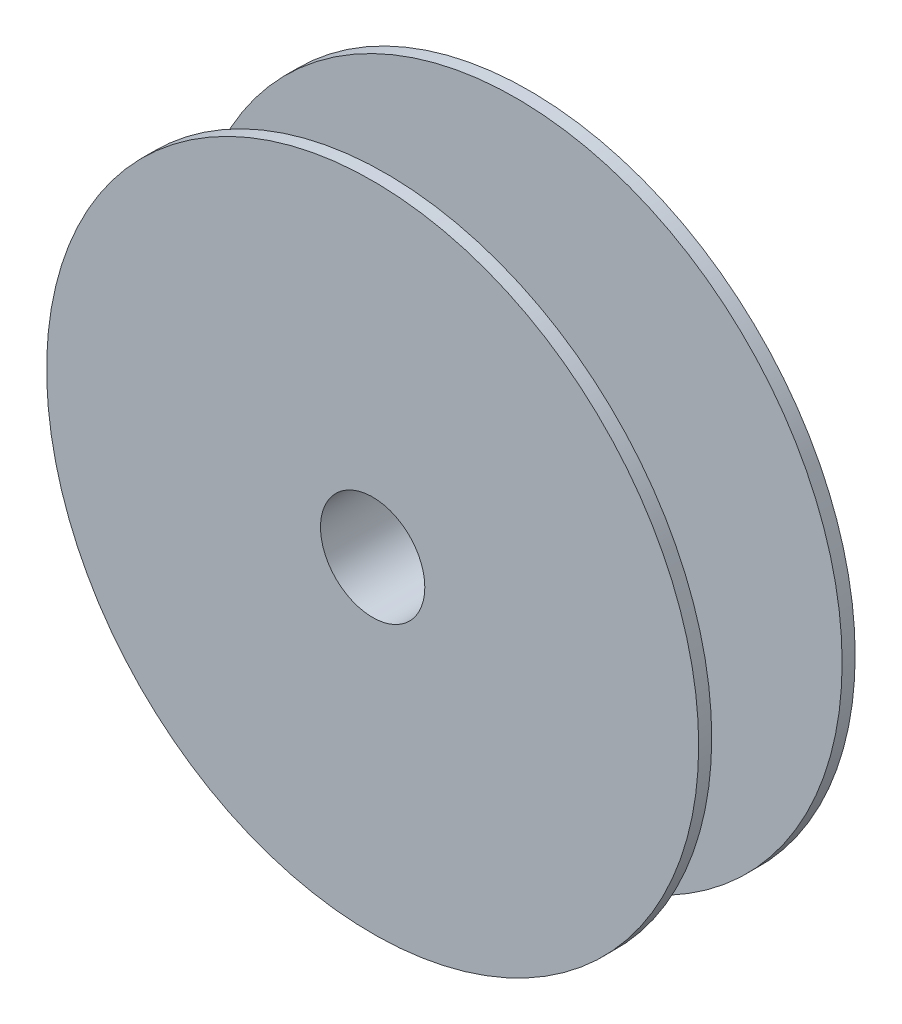
SolidWorks part; units mm, degrees
ref_plane "Front Plane" through (0, 0, 0) normal (0, 0, 1) x (1, 0, 0)
ref_plane "Top Plane" through (0, 0, 0) normal (0, 1, 0) x (1, 0, 0)
ref_plane "Right Plane" through (0, 0, 0) normal (1, 0, 0) x (0, 0, -1)
sketch "Sketch1" plane through (0, 0, 0) normal (0, 0, 1) x (1, 0, 0)
  circle A0 centre (0, 0) radius 125
  circle A1 centre (0, 0) radius 20
  dimension "D1" = 40
  dimension "D2" = 250
extrude "Boss-Extrude1" add sketch "Sketch1" along normal blind 60
shell "Shell1" thickness 5
